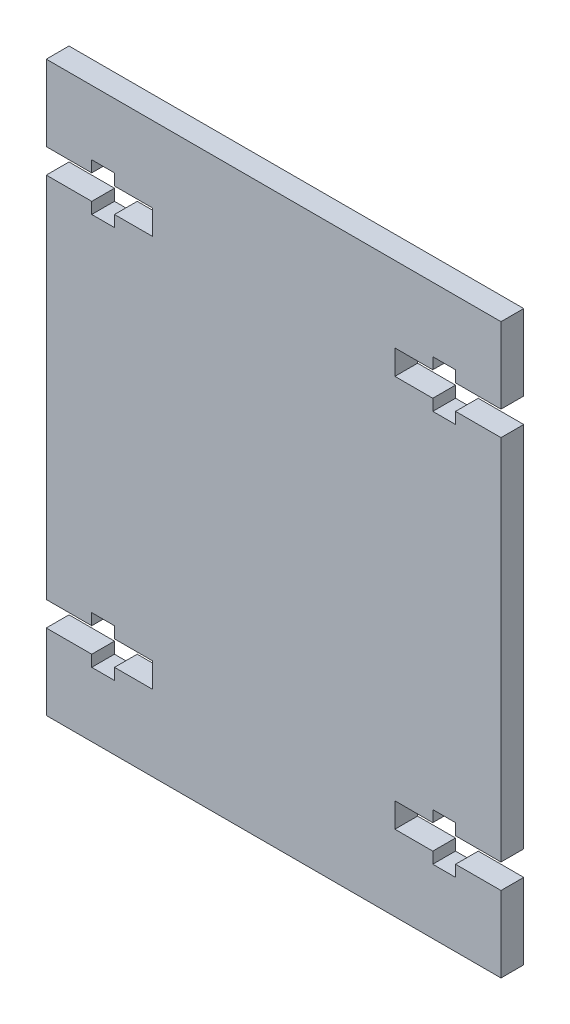
SolidWorks part; units mm, degrees
ref_plane "Front Plane" through (0, 0, 0) normal (0, 0, 1) x (1, 0, 0)
ref_plane "Top Plane" through (0, 0, 0) normal (0, 1, 0) x (1, 0, 0)
ref_plane "Right Plane" through (0, 0, 0) normal (1, 0, 0) x (0, 0, -1)
sketch "Esquisse1" plane through (0, 0, 0) normal (0, 0, 1) x (1, 0, 0)
  line L0 (-30, 37.5) -> (30, 37.5)
  line L1 (30, 37.5) -> (30, 27.5)
  line L2 (30, 12.5) -> (30, 24.25)
  line L3 (30, -12.5) -> (30, -24.25)
  line L4 (24, -29) -> (24, -27.5)
  line L5 (30, 12.5) -> (30, -12.5)
  line L6 (21, -27.5) -> (21, -29)
  line L7 (21, -22.75) -> (21, -24.25)
  line L8 (24, -24.25) -> (24, -22.75)
  line L9 (30, -27.5) -> (30, -37.5)
  line L10 (30, -37.5) -> (-30, -37.5)
  line L11 (-30, -37.5) -> (-30, -27.5)
  line L12 (30, -24.25) -> (24, -24.25)
  line L13 (24, -22.75) -> (21, -22.75)
  line L14 (21, -24.25) -> (16, -24.25)
  line L15 (-30, -12.5) -> (-30, 12.5)
  line L16 (-30, 12.5) -> (-30, 24.25)
  line L17 (-30, 0) -> (30, 0) construction
  line L18 (0, 37.5) -> (0, -37.5) construction
  line L19 (-30, 27.5) -> (-30, 37.5)
  line L20 (-30, 24.25) -> (-24, 24.25)
  line L21 (-24, 24.25) -> (-24, 22.75)
  line L22 (-24, 22.75) -> (-21, 22.75)
  line L23 (-21, 22.75) -> (-21, 24.25)
  line L24 (-21, 24.25) -> (-16, 24.25)
  line L25 (-16, 24.25) -> (-16, 27.5)
  line L26 (-16, 27.5) -> (-21, 27.5)
  line L27 (-21, 27.5) -> (-21, 29)
  line L28 (-21, 29) -> (-24, 29)
  line L29 (-24, 29) -> (-24, 27.5)
  line L30 (-24, 27.5) -> (-30, 27.5)
  line L31 (21, 22.75) -> (21, 24.25)
  line L32 (24, 24.25) -> (24, 22.75)
  line L33 (24, 29) -> (24, 27.5)
  line L34 (21, 27.5) -> (21, 29)
  line L35 (16, 24.25) -> (16, 27.5)
  line L36 (16, 27.5) -> (21, 27.5)
  line L37 (21, 24.25) -> (16, 24.25)
  line L38 (24, 22.75) -> (21, 22.75)
  line L39 (21, 29) -> (24, 29)
  line L40 (30, 24.25) -> (24, 24.25)
  line L41 (24, 27.5) -> (30, 27.5)
  line L42 (16, -24.25) -> (16, -27.5)
  line L43 (16, -27.5) -> (21, -27.5)
  line L44 (21, -29) -> (24, -29)
  line L45 (24, -27.5) -> (30, -27.5)
  line L46 (-24, -24.25) -> (-24, -22.75)
  line L47 (-21, -22.75) -> (-21, -24.25)
  line L48 (-21, -27.5) -> (-21, -29)
  line L49 (-24, -29) -> (-24, -27.5)
  line L50 (-16, -24.25) -> (-16, -27.5)
  line L51 (-21, -29) -> (-24, -29)
  line L52 (-16, -27.5) -> (-21, -27.5)
  line L53 (-21, -24.25) -> (-16, -24.25)
  line L54 (-30, -12.5) -> (-30, -24.25)
  line L55 (-24, -22.75) -> (-21, -22.75)
  line L56 (-30, -24.25) -> (-24, -24.25)
  line L57 (-24, -27.5) -> (-30, -27.5)
  line L58 (-16, 25.875) -> (-35.4388, 25.875) construction
  line L59 (-16, -25.875) -> (-34.3676, -25.875) construction
  point P63 (-16, 25.875)
  dimension "D2" = 60
  dimension "D3" = 60
  dimension "D5" = 60
  dimension "D10" = 0
  dimension "D16" = 25
  dimension "D17" = 25
  dimension "D18" = 10
  dimension "D20" = 6.25
  dimension "D21" = 1.5
  dimension "D22" = 3.25
extrude "Boss.-Extru.1" add sketch "Esquisse1" along normal blind 3
